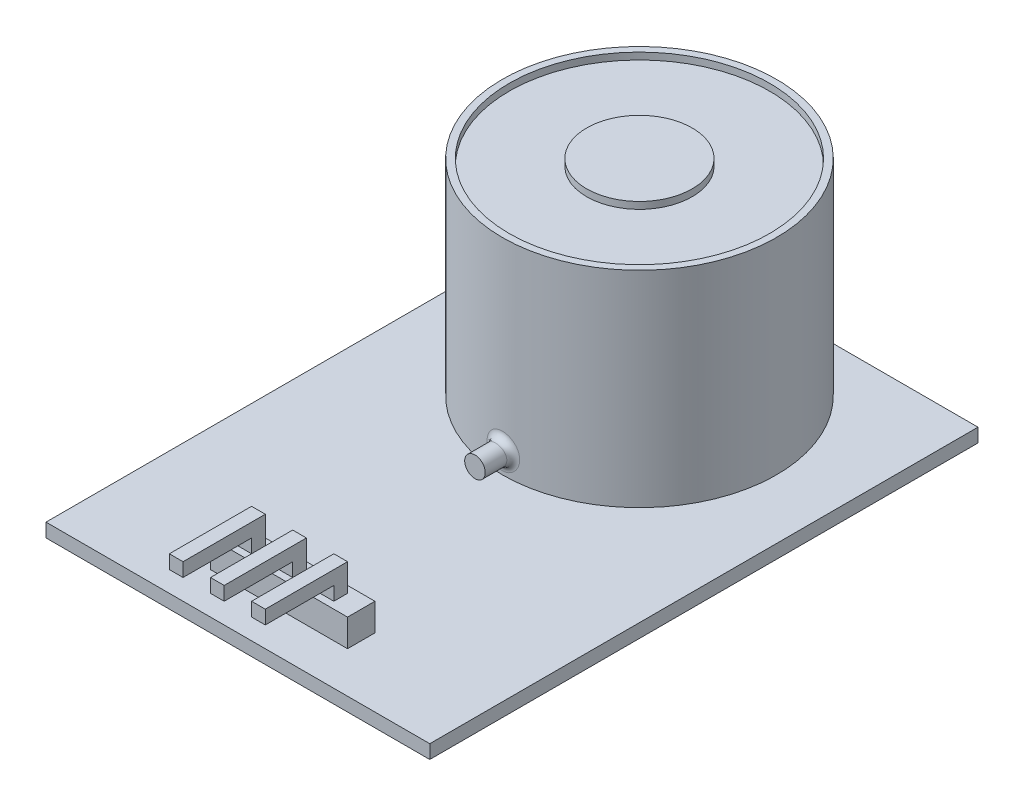
SolidWorks part; units mm, degrees
ref_plane "Plan de face" through (0, 0, 0) normal (0, 0, 1) x (1, 0, 0)
ref_plane "Plan de dessus" through (0, 0, 0) normal (0, 1, 0) x (1, 0, 0)
ref_plane "Plan de droite" through (0, 0, 0) normal (1, 0, 0) x (0, 0, -1)
sketch "Esquisse1" plane through (0, 0, 0) normal (0, 1, 0) x (1, 0, 0)
  circle A0 centre (0, 0) radius 10
  dimension "D1" = 20
extrude "Boss.-Extru.1" add sketch "Esquisse1" along normal blind 15
sketch "Esquisse2" plane through (0, 15, 0) normal (0, 1, 0) x (1, 0, 0)
  circle A0 centre (0, 0) radius 9.5
  circle A1 centre (0, 0) radius 3.85
  dimension "D1" = 7.7
  dimension "D2" = 19
extrude "Enlèv. mat.-Extru.1" cut sketch "Esquisse2" against normal blind 0.5
ref_plane "Plan1" through (0, 0, 9) normal (0, 0, 1) x (1, 0, 0)
sketch "Esquisse3" plane through (0, 0, 9) normal (0, 0, 1) x (1, 0, 0)
  circle A0 centre (0, 1.5138) radius 0.75
  dimension "D1" = 1.5
extrude "Boss.-Extru.2" add sketch "Esquisse3" along normal blind 3
fillet "Congé1" radius 0.5 1 edges at (0.7304, 1.684, 9.9733)
sketch "Esquisse4" plane through (0, 0, 0) normal (0, -1, 0) x (1, 0, 0)
  line L0 (-13.6664, 0) -> (14.3336, 0) construction
  line L1 (-13.6664, 18.6318) -> (14.3336, 18.6318)
  line L2 (-13.6664, 18.6318) -> (-13.6664, -10.3682)
  line L3 (-13.6664, -10.3682) -> (14.3336, -10.3682)
  line L4 (14.3336, 18.6318) -> (14.3336, -10.3682)
  line L7 (-13.6664, 18.6318) -> (14.3336, 18.6318)
  line L8 (-13.6664, 18.6318) -> (-13.6664, 29.6318)
  line L9 (-13.6664, 29.6318) -> (14.3336, 29.6318)
  line L10 (14.3336, 18.6318) -> (14.3336, 29.6318)
  point P0 (0, 0)
  dimension "D1" = 28
  dimension "D2" = 29
  dimension "D3" = 11
extrude "Boss.-Extru.3" add sketch "Esquisse4" along normal blind 1 contours L1 L10 L9 L8
sketch "Esquisse5" plane through (0, 0, 0) normal (0, 1, 0) x (1, 0, 0)
  line L0 (-13.6664, 10.3682) -> (-13.6664, -29.6318) construction
  line L1 (-4.6664, -26.6318) -> (5.3336, -26.6318)
  line L2 (-4.6664, -26.6318) -> (-4.6664, -24.6318)
  line L3 (-4.6664, -24.6318) -> (5.3336, -24.6318)
  line L4 (5.3336, -26.6318) -> (5.3336, -24.6318)
  line L5 (-13.6664, -29.6318) -> (14.3336, -29.6318) construction
  dimension "D1" = 10
  dimension "D2" = 9
  dimension "D3" = 3
  dimension "D4" = 2
extrude "Boss.-Extru.4" add sketch "Esquisse5" along normal blind 2
sketch "Esquisse6" plane through (0, 2, 0) normal (0, 1, 0) x (1, 0, 0)
  line L0 (-4.6664, -25.6318) -> (5.3336, -25.6318) construction
  line L1 (-4.6664, -24.6318) -> (-4.6664, -26.6318) construction
  line L2 (5.3336, -26.6318) -> (5.3336, -24.6318) construction
  line L3 (5.3336, -26.6318) -> (5.3336, -24.6318) construction
  line L4 (-3.1664, -25.1318) -> (-2.1664, -25.1318)
  line L5 (-3.1664, -25.1318) -> (-3.1664, -26.1318)
  line L6 (-3.1664, -26.1318) -> (-2.1664, -26.1318)
  line L7 (-2.1664, -25.1318) -> (-2.1664, -26.1318)
  line L8 (-3.1664, -25.1318) -> (-2.1664, -26.1318) construction
  line L9 (-3.1664, -26.1318) -> (-2.1664, -25.1318) construction
  line L10 (-0.1664, -25.1318) -> (0.8336, -25.1318)
  line L11 (-0.1664, -25.1318) -> (-0.1664, -26.1318)
  line L12 (-0.1664, -26.1318) -> (0.8336, -26.1318)
  line L13 (0.8336, -25.1318) -> (0.8336, -26.1318)
  line L14 (-0.1664, -25.1318) -> (0.8336, -26.1318) construction
  line L15 (-0.1664, -26.1318) -> (0.8336, -25.1318) construction
  line L16 (2.8336, -25.1318) -> (3.8336, -25.1318)
  line L17 (2.8336, -25.1318) -> (2.8336, -26.1318)
  line L18 (2.8336, -26.1318) -> (3.8336, -26.1318)
  line L19 (3.8336, -25.1318) -> (3.8336, -26.1318)
  line L20 (2.8336, -25.1318) -> (3.8336, -26.1318) construction
  line L21 (2.8336, -26.1318) -> (3.8336, -25.1318) construction
  point P6 (-2.6664, -25.6318)
  point P11 (0.3336, -25.6318)
  point P16 (3.3336, -25.6318)
  dimension "D1" = 1
  dimension "D2" = 1
  dimension "D3" = 1
  dimension "D4" = 1
  dimension "D5" = 1
  dimension "D6" = 1
  dimension "D7" = 1.5
  dimension "D8" = 1.5
extrude "Boss.-Extru.5" add sketch "Esquisse6" along normal blind 2
sketch "Esquisse8" plane through (0, 0, 26.1318) normal (0, 0, 1) x (1, 0, 0)
  line L0 (-3.1664, 4) -> (-3.1664, 2) construction
  line L1 (-3.1664, 4) -> (-2.1664, 4)
  line L2 (-3.1664, 4) -> (-3.1664, 3)
  line L3 (-3.1664, 3) -> (-2.1664, 3)
  line L4 (-2.1664, 4) -> (-2.1664, 3)
  line L5 (-3.1664, 4) -> (-2.1664, 4) construction
  line L6 (-2.1664, 4) -> (-2.1664, 2) construction
  line L7 (0.8336, 4) -> (0.8336, 2) construction
  line L8 (-0.1664, 4) -> (0.8336, 4)
  line L9 (-0.1664, 4) -> (-0.1664, 3)
  line L10 (-0.1664, 3) -> (0.8336, 3)
  line L11 (0.8336, 4) -> (0.8336, 3)
  line L12 (3.8336, 4) -> (3.8336, 2) construction
  line L13 (2.8336, 4) -> (3.8336, 4)
  line L14 (2.8336, 4) -> (2.8336, 3)
  line L15 (2.8336, 3) -> (3.8336, 3)
  line L16 (3.8336, 4) -> (3.8336, 3)
  dimension "D1" = 1
  dimension "D2" = 1
  dimension "D3" = 1
extrude "Boss.-Extru.6" add sketch "Esquisse8" along normal blind 5
